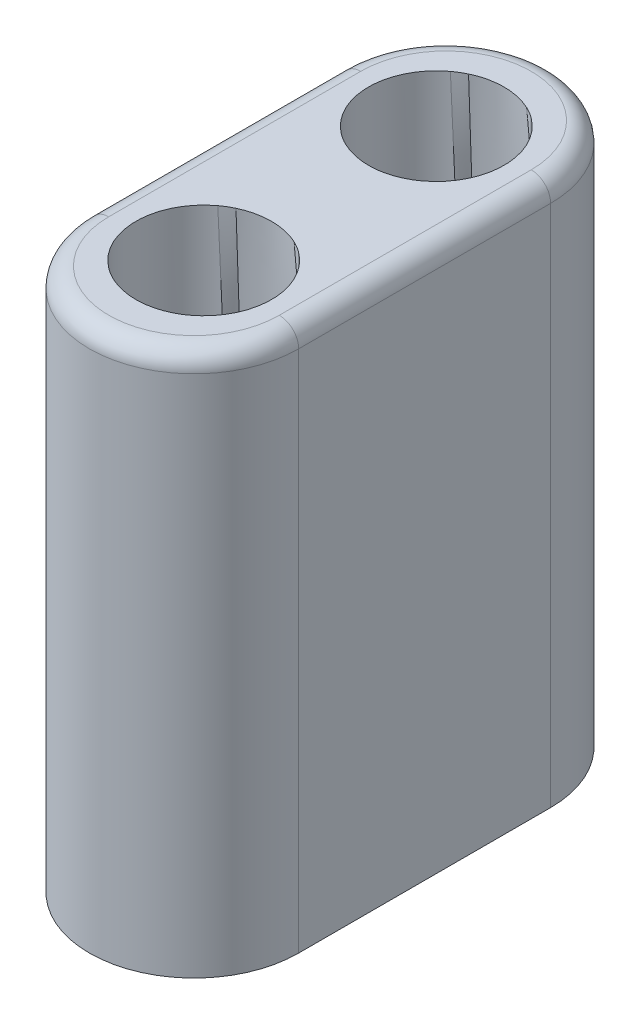
SolidWorks part; units mm, degrees
ref_plane "Plan de face" through (0, 0, 0) normal (0, 0, 1) x (1, 0, 0)
ref_plane "Plan de dessus" through (0, 0, 0) normal (0, 1, 0) x (1, 0, 0)
ref_plane "Plan de droite" through (0, 0, 0) normal (1, 0, 0) x (0, 0, -1)
sketch "Esquisse1" plane through (0, 0, 0) normal (0, 1, 0) x (1, 0, 0)
  line L0 (0, 6.5) -> (0, -6.5) construction
  line L1 (5.4, 6.5) -> (5.4, -6.5)
  line L2 (-5.4, 6.5) -> (-5.4, -6.5)
  arc A0 (5.4, 6.5) -> (-5.4, 6.5) centre (0, 6.5) ccw
  arc A1 (-5.4, -6.5) -> (5.4, -6.5) centre (0, -6.5) ccw
  point P2 (0, 0)
  dimension "D1" = 10.8
  dimension "D2" = 13
extrude "Boss.-Extru.1" add sketch "Esquisse1" along normal blind 28
fillet "Congé2" radius 1 4 edges at (0, 28, 11.9) (-5.4, 28, 0) (0, 28, -11.9) (5.4, 28, 0)
sketch "Esquisse3" plane through (0, 28, 0) normal (0, 1, 0) x (1, 0, 0)
  line L0 (0, 0) -> (0, -6) construction
  circle A0 centre (0, -6) radius 3.5
  dimension "D1" = 7
  dimension "D2" = 6
extrude "Enlèv. mat.-Extru.3" cut sketch "Esquisse3" against normal through all
ref_plane "Plan1" through (0, 18, 0) normal (0, 1, 0) x (1, 0, 0)
sketch "Esquisse4" plane through (0, 18, 0) normal (0, 1, 0) x (1, 0, 0)
  line L1 (-1.8, -2.2) -> (1.8, -2.2)
  line L2 (-1.8, -2.2) -> (-1.8, -9.8)
  line L3 (-1.8, -9.8) -> (1.8, -9.8)
  line L4 (1.8, -2.2) -> (1.8, -9.8)
  line L5 (-1.8, -2.2) -> (1.8, -9.8) construction
  line L6 (-1.8, -9.8) -> (1.8, -2.2) construction
  point P0 (0, -6)
  dimension "D1" = 7.6
  dimension "D2" = 3.6
sketch "Esquisse5" plane through (0, 28, 0) normal (0, 1, 0) x (1, 0, 0)
  circle A0 centre (0, -6) radius 3.5 construction
  circle A1 centre (0, -6) radius 3.5
loft "Enlèvement de matière-Lissage1" cut profiles "Esquisse5", "Esquisse4"
sketch "Esquisse6" plane through (0, 18, 0) normal (0, 1, 0) x (1, 0, 0)
  line L1 (-1.8, -2.2) -> (1.8, -2.2)
  line L2 (-1.8, -2.2) -> (-1.8, -9.8)
  line L3 (-1.8, -9.8) -> (1.8, -9.8)
  line L4 (1.8, -2.2) -> (1.8, -9.8)
extrude "Enlèv. mat.-Extru.4" cut sketch "Esquisse6" against normal through all
mirror "Symétrie1" about plane through (0, 0, 0) normal (0, 0, 1) of "Enlèv. mat.-Extru.3", "Enlèvement de matière-Lissage1", "Enlèv. mat.-Extru.4"
